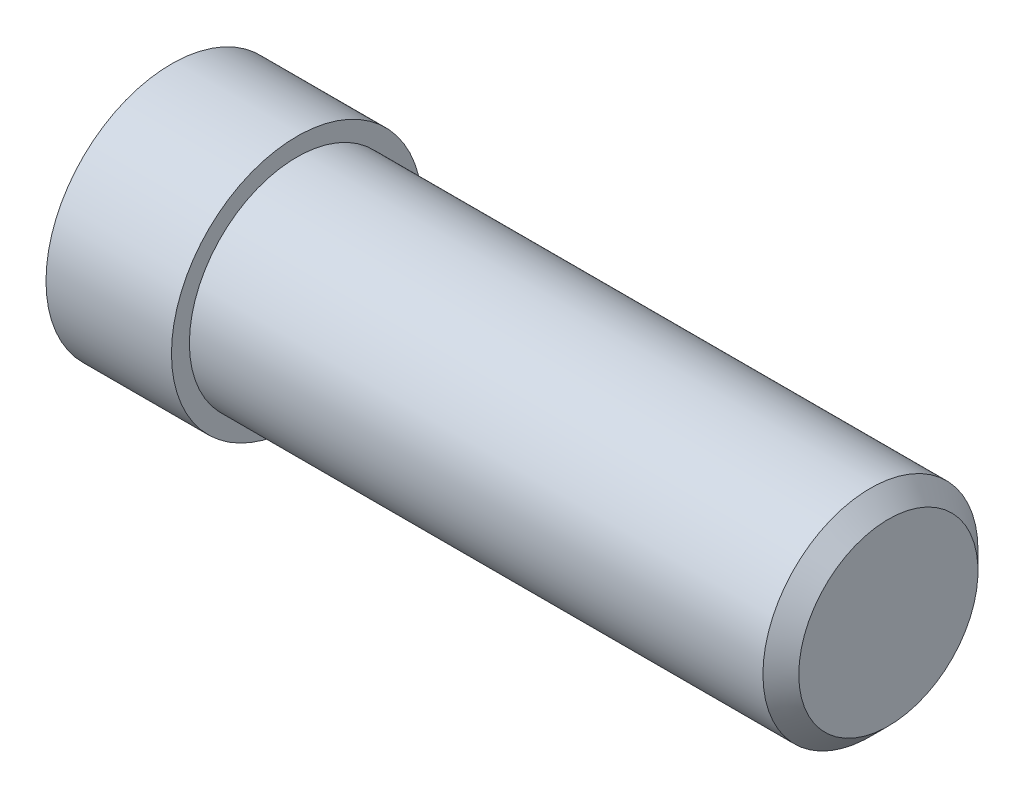
SolidWorks part; units mm, degrees
ref_plane "Front Plane" through (0, 0, 0) normal (0, 0, 1) x (1, 0, 0)
ref_plane "Top Plane" through (0, 0, 0) normal (0, 1, 0) x (1, 0, 0)
ref_plane "Right Plane" through (0, 0, 0) normal (1, 0, 0) x (0, 0, -1)
sketch "Sketch1" plane through (0, 0, 0) normal (0, 1, 0) x (1, 0, 0)
  line L0 (0, 0) -> (40, 0)
  line L1 (40, 0) -> (40, 6)
  line L2 (40, 6) -> (7, 6)
  line L3 (7, 6) -> (7, 7)
  line L4 (7, 7) -> (0, 7)
  line L5 (0, 7) -> (0, 0)
  point P7 (7, 7)
  dimension "D4" = 1
  dimension "D1" = 40
  dimension "D2" = 6
  dimension "D3" = 33
  dimension "D5" = 7
revolve "Revolve1" add sketch "Sketch1" angle 360 about L0
chamfer "Chamfer1" distance 1 angle 45 1 edges at (40, 0, 6)
